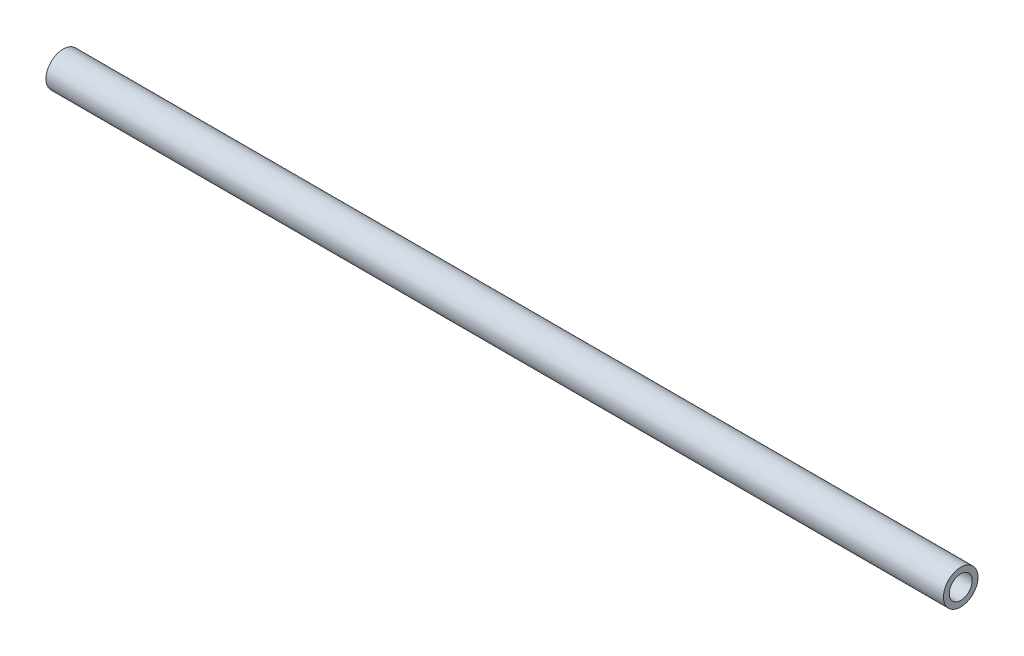
SolidWorks part; units mm, degrees
ref_plane "Front Plane" through (0, 0, 0) normal (0, 0, 1) x (1, 0, 0)
ref_plane "Top Plane" through (0, 0, 0) normal (0, 1, 0) x (1, 0, 0)
ref_plane "Right Plane" through (0, 0, 0) normal (1, 0, 0) x (0, 0, -1)
sketch "Sketch1" plane through (0, 0, 0) normal (1, 0, 0) x (0, 0, -1)
  circle A0 centre (0, 0) radius 9.525
  circle A1 centre (0, 0) radius 6.35
  dimension "D1" = 19.05
  dimension "D2" = 3.175
extrude "Boss-Extrude1" add sketch "Sketch1" against normal blind 495.3 contours A0 A1
